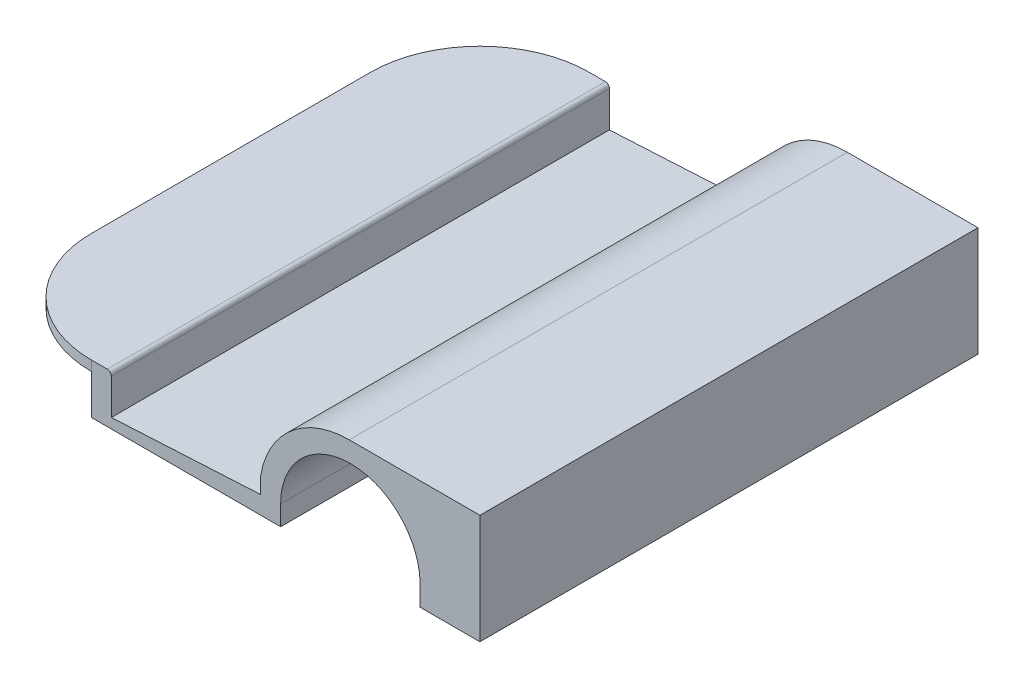
SolidWorks part; units mm, degrees
ref_plane "Plan de face" through (0, 0, 0) normal (0, 0, 1) x (1, 0, 0)
ref_plane "Plan de dessus" through (0, 0, 0) normal (0, 1, 0) x (1, 0, 0)
ref_plane "Plan de droite" through (0, 0, 0) normal (1, 0, 0) x (0, 0, -1)
sketch "Esquisse1" plane through (0, 0, 0) normal (0, 0, 1) x (1, 0, 0)
  line L0 (0, 0) -> (55, 0)
  line L1 (55, 0) -> (55, -20)
  line L2 (55, -20) -> (150, -20)
  line L3 (150, -20) -> (150, -10)
  line L4 (0, 0) -> (0, 5)
  line L5 (0, 5) -> (65, 5)
  line L6 (65, 5) -> (65, -15)
  line L8 (140, -11) -> (140, -2.6946)
  line L9 (220, -10) -> (220, -20)
  line L10 (220, -20) -> (250, -20)
  line L11 (250, -20) -> (250, 35)
  line L12 (250, 35) -> (184.403, 35)
  line L13 (140, -11) -> (65, -15)
  arc A0 (150, -10) -> (220, -10) centre (185, -10) cw
  arc A1 (184.403, 35) -> (140, -2.6946) centre (184.403, -10) ccw
  point P17 (65, -11.1176)
  dimension "D13" = 45
  dimension "D1" = 65
  dimension "D2" = 5
  dimension "D3" = 55
  dimension "D4" = 20
  dimension "D5" = 9
  dimension "D6" = 95
  dimension "D7" = 10
  dimension "D8" = 70
  dimension "D9" = 10
  dimension "D10" = 30
  dimension "D11" = 55
  dimension "D12" = 10
  dimension "D14" = 5
extrude "Boss.-Extru.1" add sketch "Esquisse1" along normal blind 250
fillet "Congé1" radius 55 2 edges at (0, 2.5, 0) (0, 2.5, 250)
fillet "Congé2" radius 2 1 edges at (65, 5, 125)
